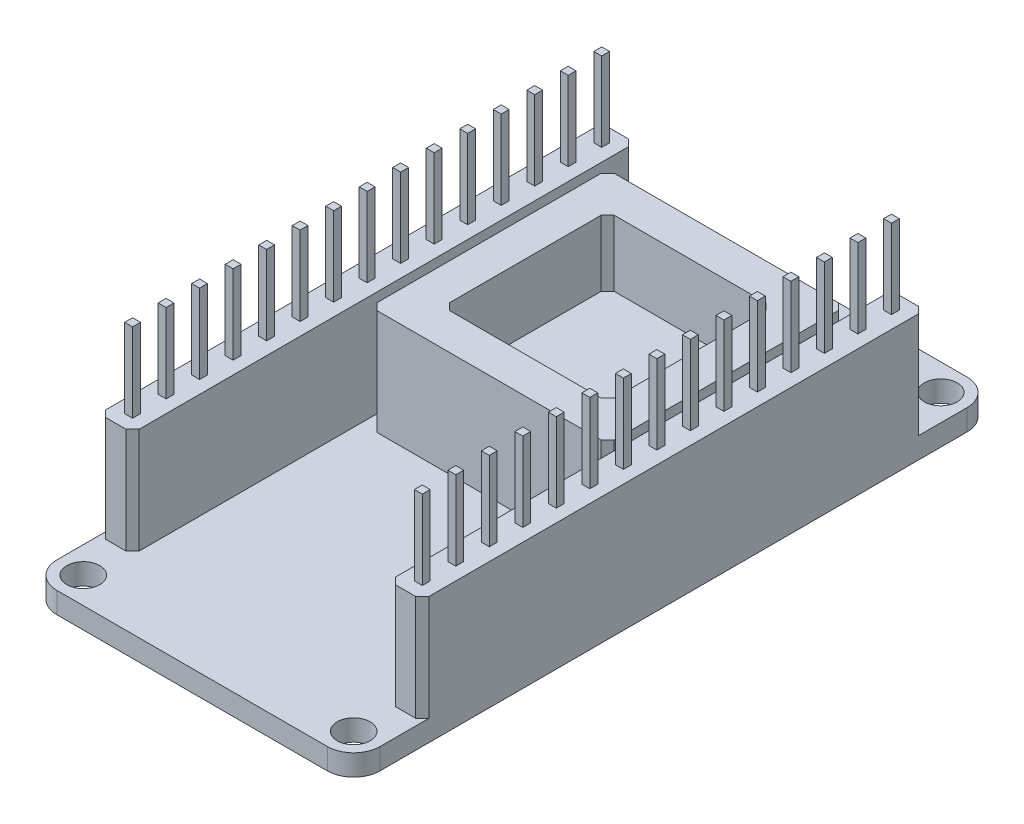
SolidWorks part; units mm, degrees
material "A-玻璃纤维"
ref_plane "前视基准面" through (0, 0, 0) normal (0, 0, 1) x (1, 0, 0)
ref_plane "上视基准面" through (0, 0, 0) normal (0, 1, 0) x (1, 0, 0)
ref_plane "右视基准面" through (0, 0, 0) normal (1, 0, 0) x (0, 0, -1)
sketch "草图1" plane through (0, 0, 0) normal (0, 1, 0) x (1, 0, 0)
  line L1 (-10.25, -24.25) -> (10.25, -24.25)
  line L2 (-12.25, -22.25) -> (-12.25, 22.25)
  line L3 (-10.25, 24.25) -> (10.25, 24.25)
  line L4 (12.25, -22.25) -> (12.25, 22.25)
  line L5 (0, 24.25) -> (0, -24.25) construction
  line L6 (-12.25, 0) -> (12.25, 0) construction
  arc A0 (12.25, 22.25) -> (10.25, 24.25) centre (10.25, 22.25) ccw
  arc A1 (10.25, -24.25) -> (12.25, -22.25) centre (10.25, -22.25) ccw
  arc A2 (-10.25, -24.25) -> (-12.25, -22.25) centre (-10.25, -22.25) cw
  arc A3 (-12.25, 22.25) -> (-10.25, 24.25) centre (-10.25, 22.25) cw
  circle A4 centre (-10.25, 22.25) radius 1.25
  circle A5 centre (10.25, 22.25) radius 1.25
  circle A6 centre (-10.25, -22.25) radius 1.25
  circle A7 centre (10.25, -22.25) radius 1.25
  point P0 (0, 0)
  point P11 (12.25, -24.25)
  point P14 (-12.25, -24.25)
  point P17 (-12.25, 24.25)
  dimension "D3" = 2
  dimension "D4" = 2.5
  dimension "D1" = 48.5
  dimension "D2" = 24.5
extrude "凸台-拉伸1" add sketch "草图1" along normal blind 1.6
sketch "草图2" plane through (0, 1.6, 0) normal (0, 1, 0) x (1, 0, 0)
  line L0 (10.25, 24.25) -> (-10.25, 24.25) construction
  line L1 (-9, -1.75) -> (9, -1.75)
  line L2 (-9, -1.75) -> (-9, 16.25)
  line L3 (-9, 16.25) -> (9, 16.25)
  line L4 (9, -1.75) -> (9, 16.25)
  line L5 (0, 16.25) -> (0, -1.75) construction
  line L6 (-9, 7.25) -> (9, 7.25) construction
  line L7 (-12.25, 22.25) -> (-12.25, -22.25) construction
  line L8 (-12.25, 19.05) -> (-9.71, 19.05)
  line L9 (-12.25, 19.05) -> (-12.25, -19.05)
  line L10 (-12.25, -19.05) -> (-9.71, -19.05)
  line L11 (-9.71, 19.05) -> (-9.71, -19.05)
  line L12 (9.71, 19.05) -> (9.71, -19.05)
  line L13 (12.25, -19.05) -> (9.71, -19.05)
  line L14 (12.25, 19.05) -> (12.25, -19.05)
  line L15 (12.25, 19.05) -> (9.71, 19.05)
  point P0 (0, 7.25)
  point P15 (-9.71, 0)
  dimension "D1" = 18
  dimension "D2" = 8
  dimension "D3" = 38.1
  dimension "D4" = 2.54
extrude "凸台-拉伸2" add sketch "草图2" along normal blind 8
sketch "草图4" plane through (0, 9.6, 0) normal (0, 1, 0) x (1, 0, 0)
  line L1 (-6.25, 1) -> (6.25, 1)
  line L2 (-6.25, 1) -> (-6.25, 13.5)
  line L3 (-6.25, 13.5) -> (6.25, 13.5)
  line L4 (6.25, 1) -> (6.25, 13.5)
  line L5 (0, 13.5) -> (0, 1) construction
  line L6 (-6.25, 7.25) -> (6.25, 7.25) construction
  point P0 (0, 7.25)
  dimension "D1" = 12.5
extrude "切除-拉伸1" cut sketch "草图4" against normal blind 5
sketch "草图5" plane through (0, 9.6, 0) normal (0, 1, 0) x (1, 0, 0)
  line L1 (-11.28, 18.08) -> (-10.68, 18.08)
  line L2 (-11.28, 18.08) -> (-11.28, 17.48)
  line L3 (-11.28, 17.48) -> (-10.68, 17.48)
  line L4 (-10.68, 18.08) -> (-10.68, 17.48)
  line L64 (-11.28, 15.54) -> (-11.28, 14.94)
  line L65 (-11.28, 15.54) -> (-10.68, 15.54)
  line L66 (-10.68, 15.54) -> (-10.68, 14.94)
  line L67 (-11.28, 14.94) -> (-10.68, 14.94)
  line L68 (-11.28, 13) -> (-11.28, 12.4)
  line L69 (-11.28, 13) -> (-10.68, 13)
  line L70 (-10.68, 13) -> (-10.68, 12.4)
  line L71 (-11.28, 12.4) -> (-10.68, 12.4)
  line L72 (-11.28, 10.46) -> (-11.28, 9.86)
  line L73 (-11.28, 10.46) -> (-10.68, 10.46)
  line L74 (-10.68, 10.46) -> (-10.68, 9.86)
  line L75 (-11.28, 9.86) -> (-10.68, 9.86)
  line L76 (-11.28, 7.92) -> (-11.28, 7.32)
  line L77 (-11.28, 7.92) -> (-10.68, 7.92)
  line L78 (-10.68, 7.92) -> (-10.68, 7.32)
  line L79 (-11.28, 7.32) -> (-10.68, 7.32)
  line L80 (-11.28, 5.38) -> (-11.28, 4.78)
  line L81 (-11.28, 5.38) -> (-10.68, 5.38)
  line L82 (-10.68, 5.38) -> (-10.68, 4.78)
  line L83 (-11.28, 4.78) -> (-10.68, 4.78)
  line L84 (-11.28, 2.84) -> (-11.28, 2.24)
  line L85 (-11.28, 2.84) -> (-10.68, 2.84)
  line L86 (-10.68, 2.84) -> (-10.68, 2.24)
  line L87 (-11.28, 2.24) -> (-10.68, 2.24)
  line L88 (-11.28, 0.3) -> (-11.28, -0.3)
  line L89 (-11.28, 0.3) -> (-10.68, 0.3)
  line L90 (-10.68, 0.3) -> (-10.68, -0.3)
  line L91 (-11.28, -0.3) -> (-10.68, -0.3)
  line L92 (-11.28, -2.24) -> (-11.28, -2.84)
  line L93 (-11.28, -2.24) -> (-10.68, -2.24)
  line L94 (-10.68, -2.24) -> (-10.68, -2.84)
  line L95 (-11.28, -2.84) -> (-10.68, -2.84)
  line L96 (-11.28, -4.78) -> (-11.28, -5.38)
  line L97 (-11.28, -4.78) -> (-10.68, -4.78)
  line L98 (-10.68, -4.78) -> (-10.68, -5.38)
  line L99 (-11.28, -5.38) -> (-10.68, -5.38)
  line L100 (-11.28, -7.32) -> (-11.28, -7.92)
  line L101 (-11.28, -7.32) -> (-10.68, -7.32)
  line L102 (-10.68, -7.32) -> (-10.68, -7.92)
  line L103 (-11.28, -7.92) -> (-10.68, -7.92)
  line L104 (-11.28, -9.86) -> (-11.28, -10.46)
  line L105 (-11.28, -9.86) -> (-10.68, -9.86)
  line L106 (-10.68, -9.86) -> (-10.68, -10.46)
  line L107 (-11.28, -10.46) -> (-10.68, -10.46)
  line L108 (-11.28, -12.4) -> (-11.28, -13)
  line L109 (-11.28, -12.4) -> (-10.68, -12.4)
  line L110 (-10.68, -12.4) -> (-10.68, -13)
  line L111 (-11.28, -13) -> (-10.68, -13)
  line L112 (-11.28, -14.94) -> (-11.28, -15.54)
  line L113 (-11.28, -14.94) -> (-10.68, -14.94)
  line L114 (-10.68, -14.94) -> (-10.68, -15.54)
  line L115 (-11.28, -15.54) -> (-10.68, -15.54)
  line L116 (-11.28, -17.48) -> (-11.28, -18.08)
  line L117 (-11.28, -17.48) -> (-10.68, -17.48)
  line L118 (-10.68, -17.48) -> (-10.68, -18.08)
  line L119 (-11.28, -18.08) -> (-10.68, -18.08)
  line L120 (-12.25, -19.05) -> (-9.71, -19.05) construction
  line L121 (-10.68, 17.78) -> (-11.28, 17.78) construction
  line L122 (-10.98, 17.78) -> (-10.98, 20.32) construction
  line L124 (-9.71, 19.05) -> (-12.25, 19.05) construction
  line L125 (0, -5.28) -> (0, 5.28) construction
  line L126 (11.28, -18.08) -> (10.68, -18.08)
  line L127 (-10.68, -17.78) -> (-11.28, -17.78) construction
  line L128 (-10.98, -17.78) -> (-10.98, -20.32) construction
  line L130 (10.68, -17.48) -> (10.68, -18.08)
  line L131 (11.28, -17.48) -> (10.68, -17.48)
  line L132 (11.28, -17.48) -> (11.28, -18.08)
  line L133 (11.28, -15.54) -> (10.68, -15.54)
  line L134 (10.68, -14.94) -> (10.68, -15.54)
  line L135 (11.28, -14.94) -> (10.68, -14.94)
  line L136 (11.28, -14.94) -> (11.28, -15.54)
  line L137 (11.28, -13) -> (10.68, -13)
  line L138 (10.68, -12.4) -> (10.68, -13)
  line L139 (11.28, -12.4) -> (10.68, -12.4)
  line L140 (11.28, -12.4) -> (11.28, -13)
  line L141 (11.28, -10.46) -> (10.68, -10.46)
  line L142 (10.68, -9.86) -> (10.68, -10.46)
  line L143 (11.28, -9.86) -> (10.68, -9.86)
  line L144 (11.28, -9.86) -> (11.28, -10.46)
  line L145 (11.28, -7.92) -> (10.68, -7.92)
  line L146 (10.68, -7.32) -> (10.68, -7.92)
  line L147 (11.28, -7.32) -> (10.68, -7.32)
  line L148 (11.28, -7.32) -> (11.28, -7.92)
  line L149 (11.28, -5.38) -> (10.68, -5.38)
  line L150 (10.68, -4.78) -> (10.68, -5.38)
  line L151 (11.28, -4.78) -> (10.68, -4.78)
  line L152 (11.28, -4.78) -> (11.28, -5.38)
  line L153 (11.28, -2.84) -> (10.68, -2.84)
  line L154 (10.68, -2.24) -> (10.68, -2.84)
  line L155 (11.28, -2.24) -> (10.68, -2.24)
  line L156 (11.28, -2.24) -> (11.28, -2.84)
  line L157 (11.28, -0.3) -> (10.68, -0.3)
  line L158 (10.68, 0.3) -> (10.68, -0.3)
  line L159 (11.28, 0.3) -> (10.68, 0.3)
  line L160 (11.28, 0.3) -> (11.28, -0.3)
  line L161 (11.28, 2.24) -> (10.68, 2.24)
  line L162 (10.68, 2.84) -> (10.68, 2.24)
  line L163 (11.28, 2.84) -> (10.68, 2.84)
  line L164 (11.28, 2.84) -> (11.28, 2.24)
  line L165 (11.28, 4.78) -> (10.68, 4.78)
  line L166 (10.68, 5.38) -> (10.68, 4.78)
  line L167 (11.28, 5.38) -> (10.68, 5.38)
  line L168 (11.28, 5.38) -> (11.28, 4.78)
  line L169 (11.28, 7.32) -> (10.68, 7.32)
  line L170 (10.68, 7.92) -> (10.68, 7.32)
  line L171 (11.28, 7.92) -> (10.68, 7.92)
  line L172 (11.28, 7.92) -> (11.28, 7.32)
  line L173 (11.28, 9.86) -> (10.68, 9.86)
  line L174 (10.68, 10.46) -> (10.68, 9.86)
  line L175 (11.28, 10.46) -> (10.68, 10.46)
  line L176 (11.28, 10.46) -> (11.28, 9.86)
  line L177 (11.28, 12.4) -> (10.68, 12.4)
  line L178 (10.68, 13) -> (10.68, 12.4)
  line L179 (11.28, 13) -> (10.68, 13)
  line L180 (11.28, 13) -> (11.28, 12.4)
  line L181 (11.28, 14.94) -> (10.68, 14.94)
  line L182 (10.68, 15.54) -> (10.68, 14.94)
  line L183 (11.28, 15.54) -> (10.68, 15.54)
  line L184 (11.28, 15.54) -> (11.28, 14.94)
  line L185 (10.68, 18.08) -> (10.68, 17.48)
  line L186 (11.28, 17.48) -> (10.68, 17.48)
  line L187 (11.28, 18.08) -> (11.28, 17.48)
  line L188 (11.28, 18.08) -> (10.68, 18.08)
  point P8 (-10.9029, -19.9681)
  point P9 (-10.98, -19.05)
  point P12 (-10.68, -16.0124)
  point P128 (-10.98, 19.9067)
  point P129 (-10.98, 19.05)
  point P140 (-10.98, -19.05)
  dimension "D1" = 0.6
  dimension "D2" = 1
  dimension "D3" = 15
extrude "凸台-拉伸3" add sketch "草图5" along normal blind 6
chamfer "倒角1" distance 0.5 angle 45 16 edges at (9, 5.6, -16.25) (9, 5.6, 1.75) (-9, 5.6, 1.75) (-9, 5.6, -16.25) (-6.25, 7.1, -13.5) (-6.25, 7.1, -1) (6.25, 7.1, -1) (6.25, 7.1, -13.5) (9.71, 5.6, -19.05) (12.25, 5.6, -19.05) (12.25, 5.6, 19.05) (9.71, 5.6, 19.05) (-9.71, 5.6, 19.05) (-12.25, 5.6, 19.05) (-9.71, 5.6, -19.05) (-12.25, 5.6, -19.05)
